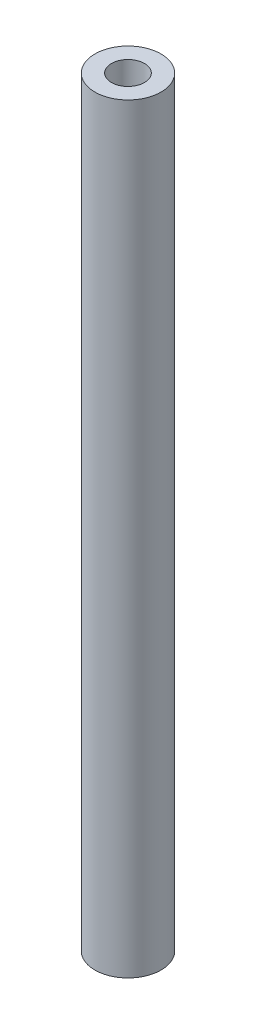
SolidWorks part; units mm, degrees
ref_plane "Front Plane" through (0, 0, 0) normal (0, 0, 1) x (1, 0, 0)
ref_plane "Top Plane" through (0, 0, 0) normal (0, 1, 0) x (1, 0, 0)
ref_plane "Right Plane" through (0, 0, 0) normal (1, 0, 0) x (0, 0, -1)
sketch "Sketch1" plane through (0, 0, 0) normal (0, 1, 0) x (1, 0, 0)
  circle A0 centre (-0.9513, -2.4621) radius 5
  circle A1 centre (-0.9513, -2.4621) radius 2.5
  dimension "D1" = 10
  dimension "D2" = 5
extrude "Boss-Extrude1" add sketch "Sketch1" along normal blind 115
